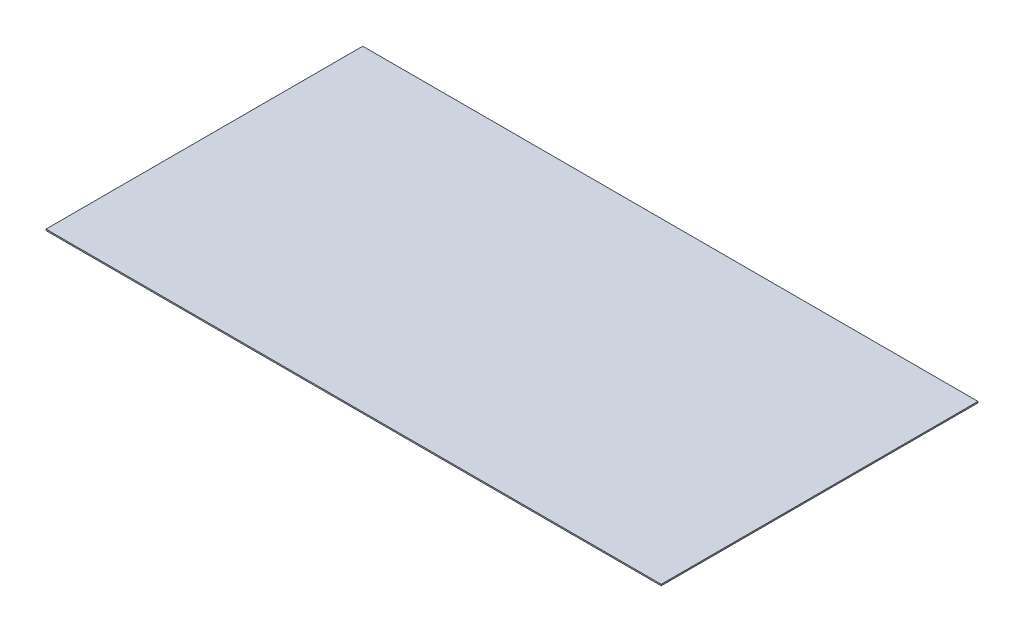
SolidWorks part; units mm, degrees
ref_plane "Front Plane" through (0, 0, 0) normal (0, 0, 1) x (1, 0, 0)
ref_plane "Top Plane" through (0, 0, 0) normal (0, 1, 0) x (1, 0, 0)
ref_plane "Right Plane" through (0, 0, 0) normal (1, 0, 0) x (0, 0, -1)
sketch "Sketch3" plane through (0, 0, 0) normal (1, 0, 0) x (0, 0, -1)
  line L1 (0, 0) -> (152.4, 0)
  line L2 (0, 0) -> (0, 0.635)
  line L3 (0, 0.635) -> (152.4, 0.635)
  line L4 (152.4, 0) -> (152.4, 0.635)
  dimension "D1" = 152.4
  dimension "D2" = 0.635
extrude "Boss-Extrude1" add sketch "Sketch3" along normal blind 296
sketch "Sketch4" plane through (296, 0, 0) normal (1, 0, 0) x (0, 0, -1)
  line L0 (76.2, 0) -> (76.2, 0.635) construction
  line L3 (0, 0) -> (152.4, 0) construction
  line L4 (152.4, 0.635) -> (0, 0.635) construction
ref_point "Point1"
